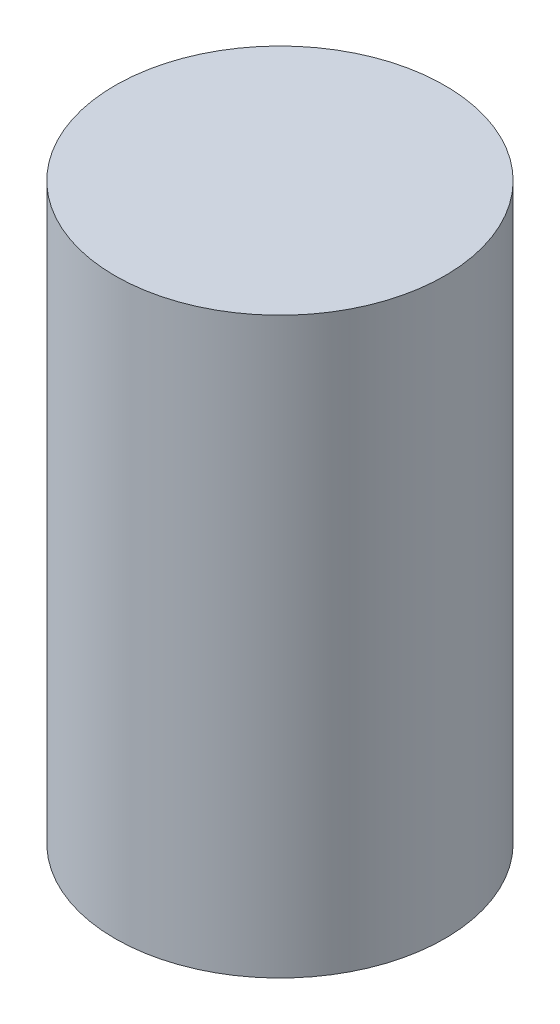
SolidWorks part; units mm, degrees
ref_plane "前视基准面" through (0, 0, 0) normal (0, 0, 1) x (1, 0, 0)
ref_plane "上视基准面" through (0, 0, 0) normal (0, 1, 0) x (1, 0, 0)
ref_plane "右视基准面" through (0, 0, 0) normal (1, 0, 0) x (0, 0, -1)
sketch "草图1" plane through (0, 0, 0) normal (0, 1, 0) x (1, 0, 0)
  circle A0 centre (0, 0) radius 15.8
  dimension "D1" = 31.6
extrude "凸台-拉伸1" add sketch "草图1" along normal blind 55
